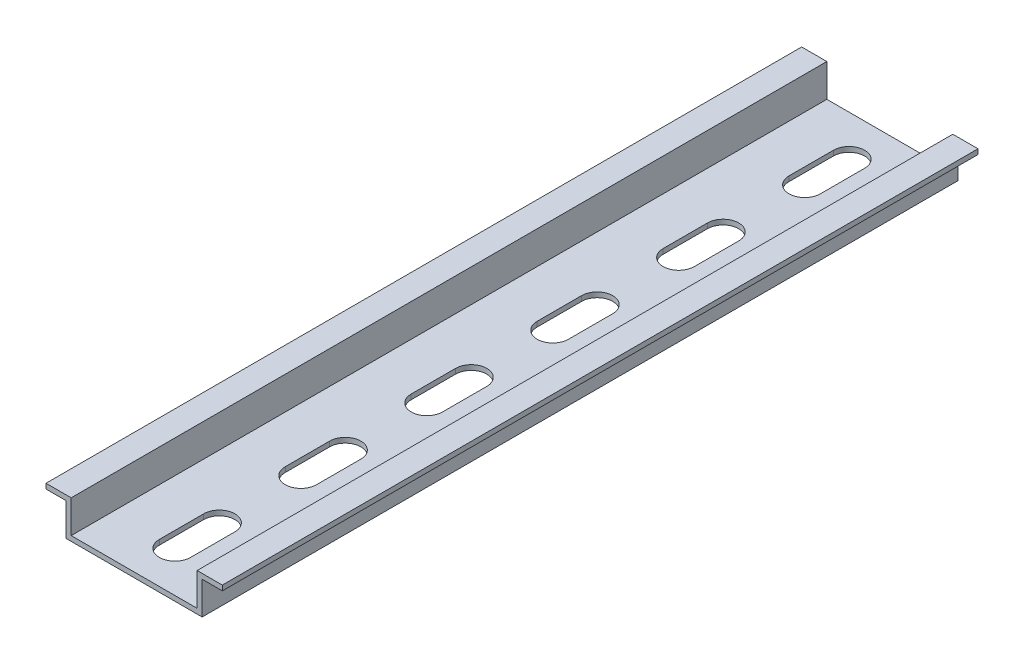
SolidWorks part; units mm, degrees
material "1060 Alloy"
ref_plane "Front Plane" through (0, 0, 0) normal (0, 0, 1) x (1, 0, 0)
ref_plane "Top Plane" through (0, 0, 0) normal (0, 1, 0) x (1, 0, 0)
ref_plane "Right Plane" through (0, 0, 0) normal (1, 0, 0) x (0, 0, -1)
sketch "Sketch1" plane through (0, 0, 0) normal (0, 0, 1) x (1, 0, 0)
  line L0 (0, 0) -> (13.5, 0)
  line L1 (13.5, 0) -> (13.5, 6.5)
  line L2 (13.5, 6.5) -> (17.5, 6.5)
  line L3 (17.5, 6.5) -> (17.5, 7.5)
  line L4 (17.5, 7.5) -> (12.5, 7.5)
  line L5 (12.5, 7.5) -> (12.5, 1)
  line L6 (12.5, 1) -> (0, 1)
  line L7 (0, 1) -> (0, 0)
  line L8 (13.5, 6.5) -> (12.5, 6.5) construction
  dimension "D1" = 1
  dimension "D2" = 13.5
  dimension "D3" = 6.5
  dimension "D4" = 4
extrude "Boss-Extrude1" add sketch "Sketch1" along normal blind 150
sketch "Sketch2" plane through (0, 0, 0) normal (0, 1, 0) x (1, 0, 0)
  line L0 (0, -8.1) -> (0, -16.9) construction
  line L1 (3.1, -8.1) -> (3.1, -16.9)
  line L2 (-3.1, -8.1) -> (-3.1, -16.9)
  line L3 (0, -150) -> (0, 0) construction
  arc A0 (3.1, -8.1) -> (-3.1, -8.1) centre (0, -8.1) ccw
  arc A1 (-3.1, -16.9) -> (3.1, -16.9) centre (0, -16.9) ccw
  point P2 (0, -12.5)
  dimension "D2" = 3.1
  dimension "D1" = 8.8
  dimension "D3" = 12.5
extrude "Cut-Extrude1" cut sketch "Sketch2" along normal through all
pattern_linear "LPattern1" count 6 spacing 25 along (0, 0, 1) of "Cut-Extrude1"
mirror "Mirror2" about plane through (0, 0, 0) normal (1, 0, 0) of "LPattern1", "Cut-Extrude1", "Boss-Extrude1"
